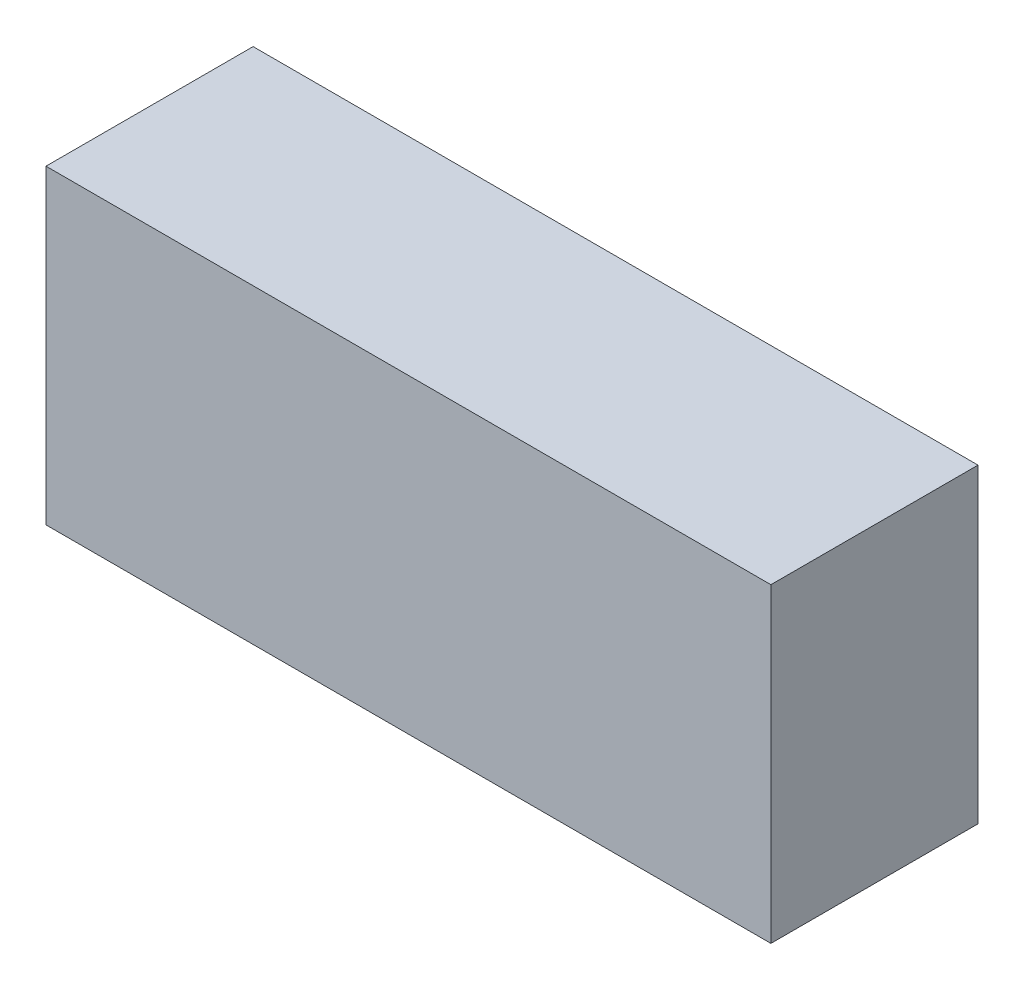
SolidWorks part; units mm, degrees
ref_plane "Plan de face" through (0, 0, 0) normal (0, 0, 1) x (1, 0, 0)
ref_plane "Plan de dessus" through (0, 0, 0) normal (0, 1, 0) x (1, 0, 0)
ref_plane "Plan de droite" through (0, 0, 0) normal (1, 0, 0) x (0, 0, -1)
sketch "Esquisse1" plane through (0, 0, 0) normal (0, 0, 1) x (1, 0, 0)
  line L1 (0, 0) -> (70, 0)
  line L2 (0, 0) -> (0, 30)
  line L3 (0, 30) -> (70, 30)
  line L4 (70, 0) -> (70, 30)
  dimension "D1" = 70
  dimension "D2" = 30
extrude "Boss.-Extru.1" add sketch "Esquisse1" along normal blind 20
